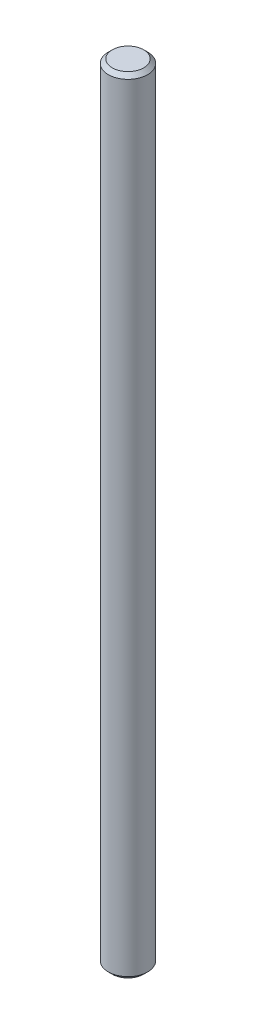
SolidWorks part; units mm, degrees
ref_plane "Front Plane" through (0, 0, 0) normal (0, 0, 1) x (1, 0, 0)
ref_plane "Top Plane" through (0, 0, 0) normal (0, 1, 0) x (1, 0, 0)
ref_plane "Right Plane" through (0, 0, 0) normal (1, 0, 0) x (0, 0, -1)
sketch "Sketch1" plane through (0, 0, 0) normal (0, 1, 0) x (1, 0, 0)
  circle A0 centre (0, 0) radius 4
  dimension "D1" = 8
extrude "Boss-Extrude1" add sketch "Sketch1" along normal blind 160
chamfer "Chamfer1" distance 0.8 angle 45 2 edges at (0, 0, 4) (0, 160, 4)
equation "\"D\"= 8"
equation "\"L\"= 160"
equation "\"D1@Sketch1\"=\"D\""
equation "\"D1@Boss-Extrude1\"=\"L\""
equation "\"D1@Chamfer1\"=\"D\"/10"
